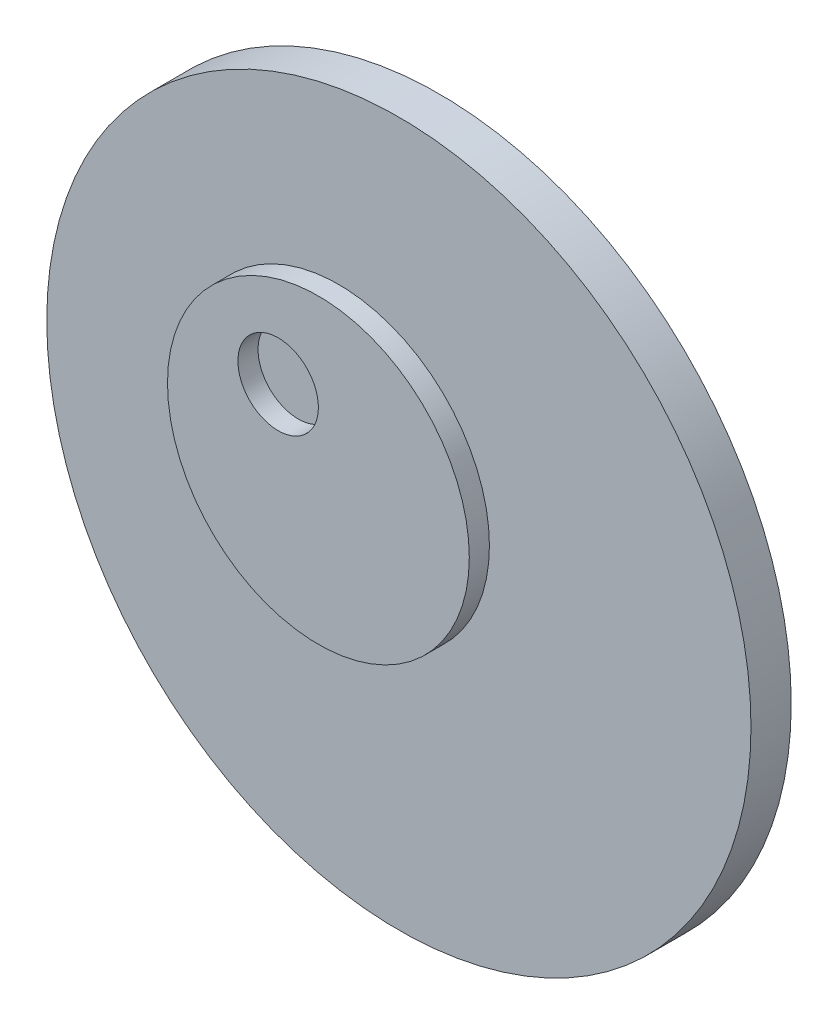
SolidWorks part; units mm, degrees
ref_plane "Front Plane" through (0, 0, 0) normal (0, 0, 1) x (1, 0, 0)
ref_plane "Top Plane" through (0, 0, 0) normal (0, 1, 0) x (1, 0, 0)
ref_plane "Right Plane" through (0, 0, 0) normal (1, 0, 0) x (0, 0, -1)
sketch "Sketch1" plane through (0, 0, 0) normal (0, 0, 1) x (1, 0, 0)
  circle A0 centre (0, 0) radius 17.5
  dimension "D1" = 35
extrude "Boss-Extrude1" add sketch "Sketch1" along normal blind 2 contours A0
sketch "Sketch2" plane through (0, 0, 2) normal (0, 0, 1) x (1, 0, 0)
  circle A0 centre (-3, 1.3) radius 7.5
  circle A1 centre (-5, 4) radius 2
  dimension "D1" = 15
  dimension "D4" = 4
  dimension "D2" = 1.3
  dimension "D3" = 3
  dimension "D5" = 5
  dimension "D6" = 4
extrude "Boss-Extrude2" add sketch "Sketch2" along normal blind 1 separate body contours A0 A1
